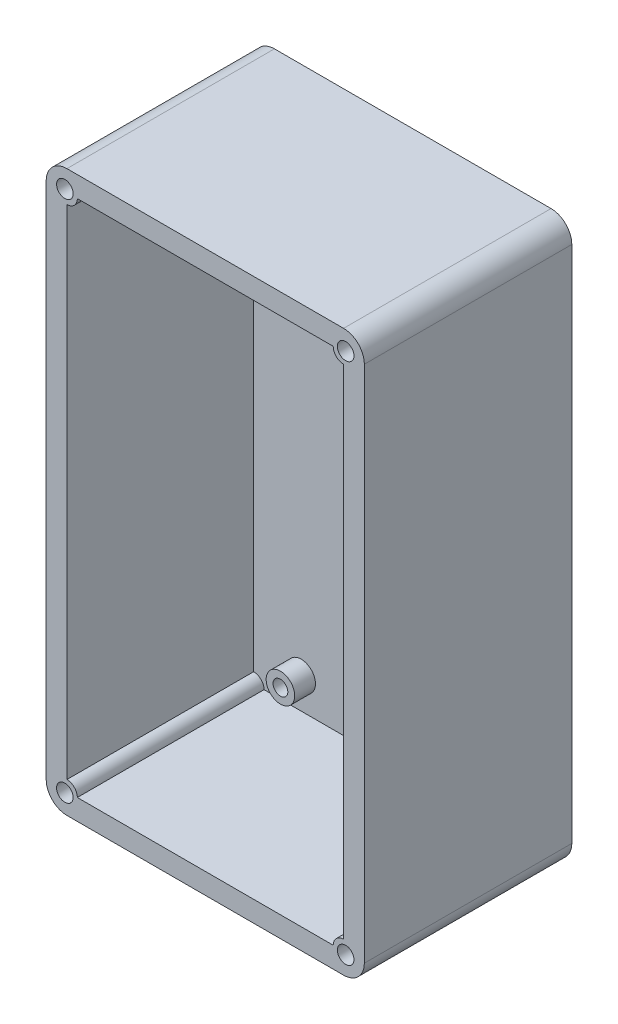
SolidWorks part; units mm, degrees
ref_plane "Front Plane" through (0, 0, 0) normal (0, 0, 1) x (1, 0, 0)
ref_plane "Top Plane" through (0, 0, 0) normal (0, 1, 0) x (1, 0, 0)
ref_plane "Right Plane" through (0, 0, 0) normal (1, 0, 0) x (0, 0, -1)
sketch "Sketch1" plane through (0, 0, 0) normal (0, 0, 1) x (1, 0, 0)
  line L0 (0, 37.5) -> (0, -37.5) construction
  line L1 (-20, -37.5) -> (20, -37.5)
  line L2 (-20, -37.5) -> (-20, 37.5)
  line L3 (-20, 37.5) -> (20, 37.5)
  line L4 (20, -37.5) -> (20, 37.5)
  line L5 (-13.13, -33.06) -> (13.13, -33.06) construction
  line L6 (-13.13, -33.06) -> (-13.13, 33.06) construction
  line L7 (-13.13, 33.06) -> (13.13, 33.06) construction
  line L8 (13.13, -33.06) -> (13.13, 33.06) construction
  line L9 (-13.13, -33.06) -> (13.13, 33.06) construction
  line L10 (-13.13, 33.06) -> (13.13, -33.06) construction
  line L11 (0, 0) -> (-13.13, 0) construction
  line L12 (20, 0) -> (-20, 0) construction
  circle A0 centre (13.13, 33.06) radius 1.065
  circle A1 centre (-13.13, 33.06) radius 1.065
  circle A2 centre (-13.13, -33.06) radius 1.065
  circle A3 centre (13.13, -33.06) radius 1.065
  point P0 (0, 0)
  point P6 (0, 0)
  dimension "D5" = 2.13
  dimension "D1" = 75
  dimension "D2" = 40
  dimension "D3" = 26.26
  dimension "D4" = 66.12
extrude "Boss-Extrude1" add sketch "Sketch1" along normal blind 3
sketch "Sketch2" plane through (0, 0, 3) normal (0, 0, 1) x (1, 0, 0)
  line L0 (0, 37.5) -> (0, -37.5) construction
  line L1 (20, 37.5) -> (-20, 37.5) construction
  line L2 (-20, -37.5) -> (20, -37.5) construction
  line L3 (-20, 0) -> (20, 0) construction
  line L4 (-20, 37.5) -> (-20, -37.5) construction
  line L5 (20, -37.5) -> (20, 37.5) construction
  circle A0 centre (-13.13, 33.06) radius 1.065
  circle A3 centre (-13.13, 33.06) radius 2.065
  circle A4 centre (13.13, 33.06) radius 2.065
  circle A5 centre (13.13, 33.06) radius 1.065
  circle A6 centre (13.13, -33.06) radius 1.065
  circle A7 centre (13.13, -33.06) radius 2.065
  circle A8 centre (-13.13, -33.06) radius 2.065
  circle A9 centre (-13.13, -33.06) radius 1.065
  dimension "D1" = 1
extrude "Boss-Extrude2" add sketch "Sketch2" along normal blind 3
sketch "Sketch4" plane through (0, 0, 0) normal (0, 0, -1) x (-1, 0, 0)
  line L0 (0, 0) -> (0, -37.5) construction
  line L1 (-18.5, -37.5) -> (18.5, -37.5)
  line L2 (-20, -36) -> (-20, 36)
  line L3 (-18.5, 37.5) -> (18.5, 37.5)
  line L4 (20, -36) -> (20, 36)
  line L5 (-20, -37.5) -> (20, 37.5) construction
  line L6 (-20, 37.5) -> (20, -37.5) construction
  line L7 (-23, -40.5) -> (23, -40.5)
  line L8 (-23, -40.5) -> (-23, 40.5)
  line L9 (-23, 40.5) -> (23, 40.5)
  line L10 (23, -40.5) -> (23, 40.5)
  line L11 (-23, -40.5) -> (23, 40.5) construction
  line L12 (-23, 40.5) -> (23, -40.5) construction
  line L13 (0, 0) -> (-20, 0) construction
  arc A0 (20, -36) -> (18.5, -37.5) centre (20, -37.5) ccw
  arc A1 (-20, -36) -> (-18.5, -37.5) centre (-20, -37.5) cw
  arc A2 (20, 36) -> (18.5, 37.5) centre (20, 37.5) cw
  arc A3 (-20, 36) -> (-18.5, 37.5) centre (-20, 37.5) ccw
  point P0 (0, 0)
  point P7 (0, 0)
  point P12 (0, 40.5)
  dimension "D3" = 3
  dimension "D1" = 3
  dimension "D2" = 3
extrude "Boss-Extrude3" add sketch "Sketch4" against normal blind 30
sketch "Sketch5" plane through (0, 0, 3) normal (0, 0, 1) x (1, 0, 0)
  line L1 (-4, -6) -> (4, -6)
  line L2 (-4, -6) -> (-4, 6)
  line L3 (-4, 6) -> (4, 6)
  line L4 (4, -6) -> (4, 6)
  line L5 (-4, -6) -> (4, 6) construction
  line L6 (-4, 6) -> (4, -6) construction
  point P0 (0, 0)
  dimension "D1" = 12
  dimension "D2" = 8
extrude "Cut-Extrude1" cut sketch "Sketch5" against normal blind 25
fillet "Fillet2" radius 2 4 edges at (-4, 6, 1.5) (4, 6, 1.5) (4, -6, 1.5) (-4, -6, 1.5)
sketch "Sketch6" plane through (0, 0, 30) normal (0, 0, 1) x (1, 0, 0)
  line L0 (0, 40.5) -> (0, 0) construction
  line L1 (-23, 40.5) -> (23, 40.5) construction
  line L2 (0, 0) -> (23, 0) construction
  line L3 (23, 40.5) -> (23, -40.5) construction
  line L4 (-23, -40.5) -> (-23, 40.5) construction
  circle A0 centre (-20.3, 37.8) radius 1.2
  circle A1 centre (20.3, 37.8) radius 1.2
  circle A2 centre (20.3, -37.8) radius 1.2
  circle A3 centre (-20.3, -37.8) radius 1.2
  point P17 (0, 0)
  point P20 (-21.2196, 36.6103)
  dimension "D1" = 2.4
  dimension "D3" = 2.7
  dimension "D2" = 2.7
extrude "Cut-Extrude2" cut sketch "Sketch6" against normal blind 20
sketch "Sketch7" plane through (0, 0, 3) normal (0, 0, 1) x (1, 0, 0)
  line L0 (0, 37.5) -> (0, 0) construction
  line L3 (18.5, 37.5) -> (-18.5, 37.5) construction
  line L4 (0, 0) -> (20, 0) construction
  line L5 (20, 36) -> (20, -36) construction
  circle A0 centre (0, 18.75) radius 1.65
  circle A1 centre (0, -18.75) radius 1.65
  dimension "D1" = 3.3
extrude "Cut-Extrude3" cut sketch "Sketch7" against normal blind 20
sketch "Sketch8" plane through (0, 0, 3) normal (0, 0, 1) x (1, 0, 0)
  circle A0 centre (0, 18.75) radius 2.5
  circle A1 centre (0, -18.75) radius 2.5
  dimension "D1" = 5
  dimension "D2" = 5
extrude "Cut-Extrude4" cut sketch "Sketch8" against normal blind 2.5
fillet "Fillet3" radius 3 4 edges at (23, 40.5, 15) (-23, 40.5, 15) (-23, -40.5, 15) (23, -40.5, 15)
